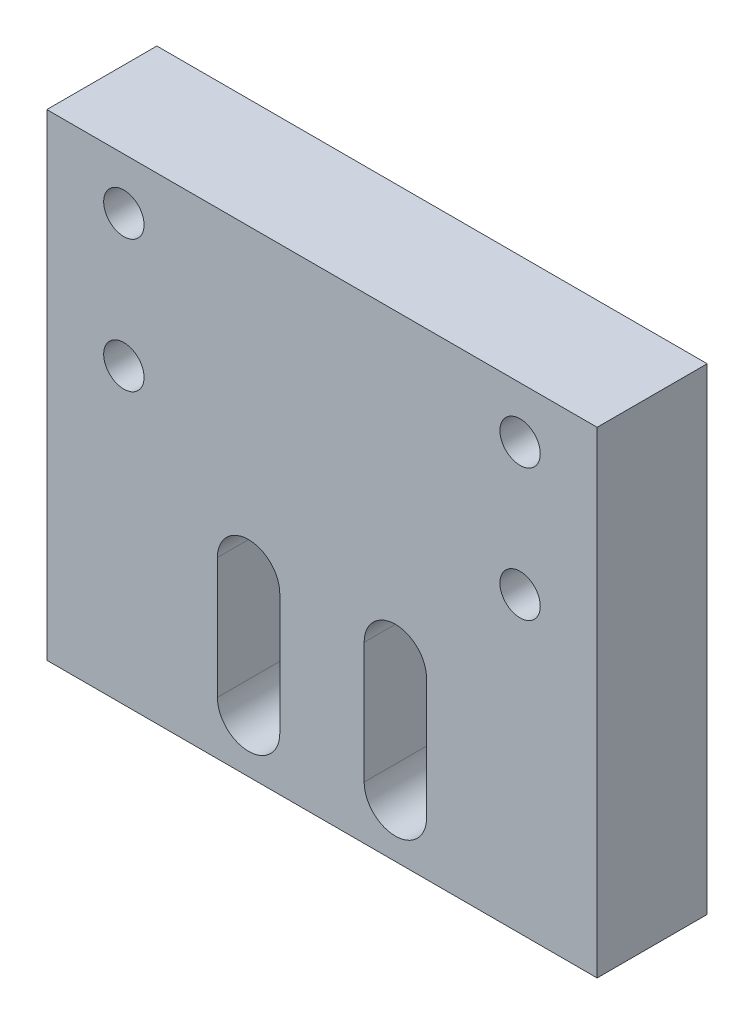
SolidWorks part; units mm, degrees
ref_plane "Front Plane" through (0, 0, 0) normal (0, 0, 1) x (1, 0, 0)
ref_plane "Top Plane" through (0, 0, 0) normal (0, 1, 0) x (1, 0, 0)
ref_plane "Right Plane" through (0, 0, 0) normal (1, 0, 0) x (0, 0, -1)
sketch "Sketch1" plane through (0, 0, 0) normal (0, 0, 1) x (1, 0, 0)
  line L0 (10, -15.5788) -> (-10, -15.5788) construction
  line L1 (-37.5, 33.9212) -> (37.5, 33.9212)
  line L2 (-37.5, 33.9212) -> (-37.5, -31.0788)
  line L3 (-37.5, -31.0788) -> (37.5, -31.0788)
  line L4 (37.5, 33.9212) -> (37.5, -31.0788)
  line L5 (-10, -7.3288) -> (-10, -23.8288) construction
  line L6 (-27, 26.9212) -> (27, 26.9212) construction
  line L7 (-27, 26.9212) -> (-27, 8.9212) construction
  line L8 (-27, 8.9212) -> (27, 8.9212) construction
  line L9 (27, 26.9212) -> (27, 8.9212) construction
  line L10 (-5.75, -7.3288) -> (-5.75, -23.8288)
  line L11 (-14.25, -7.3288) -> (-14.25, -23.8288)
  line L12 (10, -7.3288) -> (10, -23.8288) construction
  line L13 (14.25, -7.3288) -> (14.25, -23.8288)
  line L14 (5.75, -7.3288) -> (5.75, -23.8288)
  circle A0 centre (-27, 8.9212) radius 2.75
  circle A1 centre (-27, 26.9212) radius 2.75
  circle A2 centre (27, 26.9212) radius 2.75
  circle A3 centre (27, 8.9212) radius 2.75
  arc A4 (-5.75, -7.3288) -> (-14.25, -7.3288) centre (-10, -7.3288) ccw
  arc A5 (-14.25, -23.8288) -> (-5.75, -23.8288) centre (-10, -23.8288) ccw
  arc A6 (14.25, -7.3288) -> (5.75, -7.3288) centre (10, -7.3288) ccw
  arc A7 (5.75, -23.8288) -> (14.25, -23.8288) centre (10, -23.8288) ccw
  point P0 (0, 0)
  point P6 (0, 33.9212)
  point P13 (0, 26.9212)
  point P15 (0, -15.5788)
  point P21 (-10, -15.5788)
  point P30 (10, -15.5788)
  point P36 (-10, -28.0788)
  point P37 (-10, -3.0788)
  dimension "D8" = 5.5
  dimension "D9" = 4.25
  dimension "D1" = 75
  dimension "D2" = 65
  dimension "D3" = 7
  dimension "D4" = 54
  dimension "D5" = 18
  dimension "D6" = 30
  dimension "D7" = 20
  dimension "D10" = 3
extrude "Boss-Extrude1" add sketch "Sketch1" along normal blind 15
